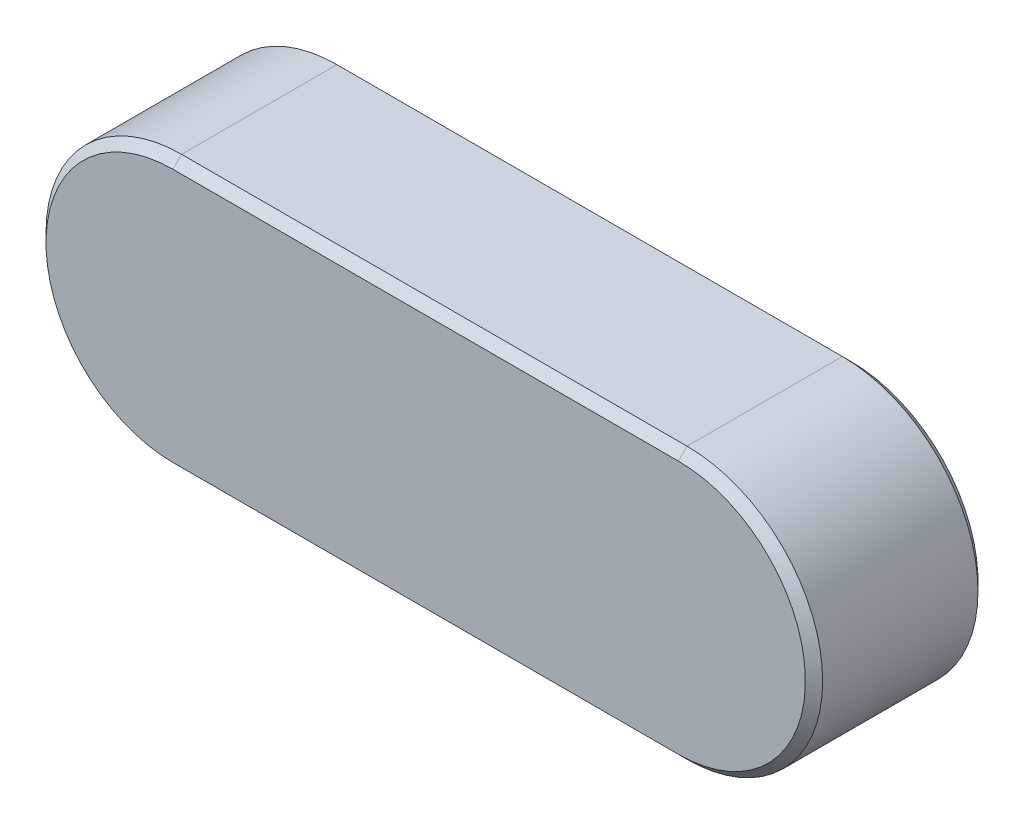
SolidWorks part; units mm, degrees
ref_plane "Plane XY" through (0, 0, 0) normal (0, 0, 1) x (1, 0, 0)
ref_plane "Plane ZX" through (0, 0, 0) normal (0, 1, 0) x (1, 0, 0)
ref_plane "Plane YZ" through (0, 0, 0) normal (1, 0, 0) x (0, 0, -1)
sketch "Schizzo1" plane through (0, 0, 0) normal (0, 0, 1) x (1, 0, 0)
  line L0 (-38.2171, 0) -> (42.24, 0) construction
  line L1 (-20.5, 0) -> (20.5, 0) construction
  line L2 (-20.5, 11) -> (20.5, 11)
  line L3 (-20.5, -11) -> (20.5, -11)
  arc A0 (-20.5, 11) -> (-20.5, -11) centre (-20.5, 0) ccw
  arc A1 (20.5, -11) -> (20.5, 11) centre (20.5, 0) ccw
  point P5 (0, 0)
  dimension "D1" = 11
  dimension "D2" = 41
  dimension "D3" = 20.5
extrude "Estrusione-Estrusione1" add sketch "Schizzo1" along normal blind 14
chamfer "Smusso1" distance 0.7 angle 45 8 edges at (-31.5, 0, 0) (0, -11, 0) (31.5, 0, 0) (0, 11, 0) (-31.5, 0, 14) (0, -11, 14) (0, 11, 14) (31.5, 0, 14)
